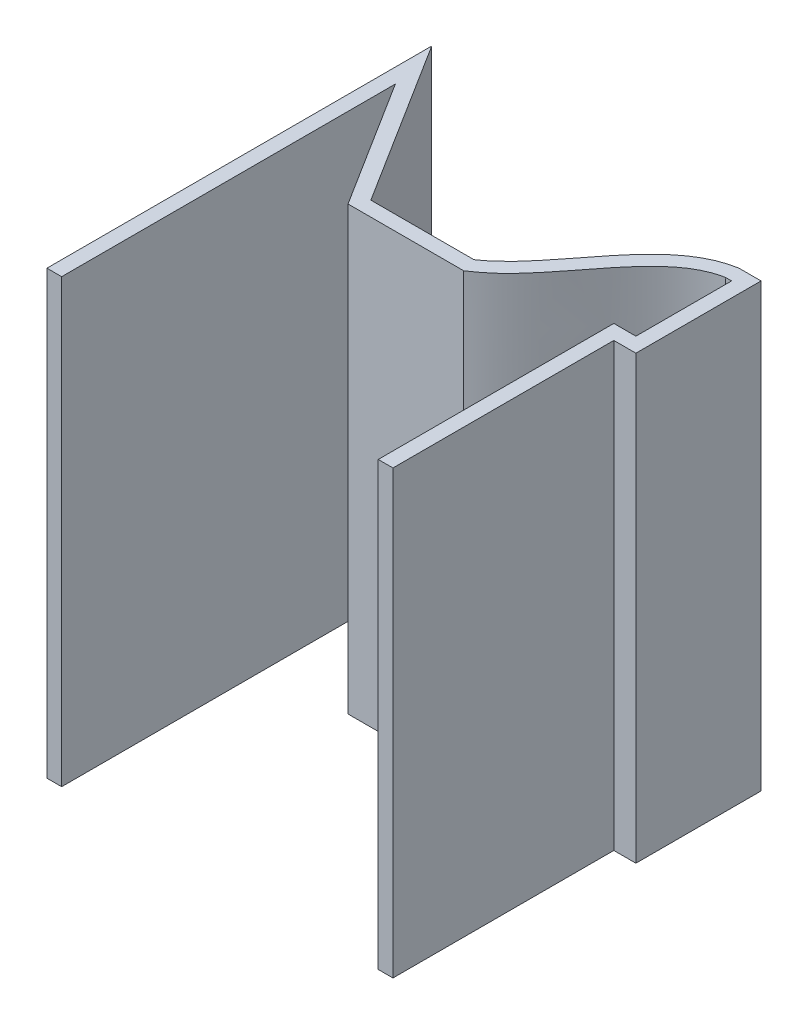
SolidWorks part; units mm, degrees
ref_plane "Front Plane" through (0, 0, 0) normal (0, 0, 1) x (1, 0, 0)
ref_plane "Top Plane" through (0, 0, 0) normal (0, 1, 0) x (1, 0, 0)
ref_plane "Right Plane" through (0, 0, 0) normal (1, 0, 0) x (0, 0, -1)
sketch "Sketch1" plane through (0, 0, 0) normal (0, 1, 0) x (1, 0, 0)
  line L3 (3, 47) -> (3, 30)
  line L4 (3, 30) -> (0, 30)
  line L5 (0, 0) -> (0, 30)
  line L6 (0, 47) -> (3, 47)
  line L9 (-33, 30) -> (-19, 30)
  line L23 (-47, 52.2684) -> (-33, 30)
  line L25 (-45, 0) -> (-45, 45.3295)
  line L26 (-45, 45.3295) -> (-34.105, 28)
  line L27 (-34.105, 28) -> (-18.3864, 28)
  line L28 (-47, 0) -> (-47, 52.2684)
  line L29 (0.1761, 45) -> (1, 45)
  line L30 (1, 45) -> (1, 32)
  line L31 (1, 32) -> (-2, 32)
  line L32 (-2, 0) -> (-2, 32)
  line L33 (-47, 0) -> (-45, 0)
  line L34 (-2, 0) -> (0, 0)
  spline S0 degree 3 poles (0, 47) (-8.7358, 45.5223) (-12.4112, 34.4627) (-19, 30) knots 0 0 0 0 1 1 1 1
  spline S1 degree 1 poles (0.1761, 45) (-18.3864, 28) knots 0 0 1 1 construction
  spline S2 degree 3 poles (-18.3864, 28) (-18.2816, 28.071) (-18.076, 28.2106) (-17.632, 28.509) (-16.7888, 29.1278) (-15.2661, 30.4367) (-13.2818, 32.5788) (-11.1163, 35.3224) (-8.328, 38.9716) (-4.7963, 42.9893) (-1.6054, 44.6674) (0.1761, 45) knots 0.007316 0.007316 0.007316 0.007316 0.023228 0.03914 0.070965 0.134614 0.261912 0.38921 0.516508 0.771104 1.025701 1.025701 1.025701 1.025701
  point P1 (-52, 0)
extrude "Boss-Extrude12" add sketch "Sketch1" along normal blind 60
sketch "Sketch2" plane through (0, 0, -30) normal (0, 0, -1) x (-1, 0, 0)
  line L0 (19, 60) -> (33, 60) construction
  line L1 (19, 60) -> (19, 0) construction
  line L2 (33, 0) -> (19, 0)
  line L3 (33, 0) -> (33, 2.424)
  line L5 (19, 0) -> (19, 2.424)
  arc A0 (19, 2.424) -> (33, 2.424) centre (26, 60) ccw
extrude "Boss-Extrude13" add sketch "Sketch2" along normal blind 8
